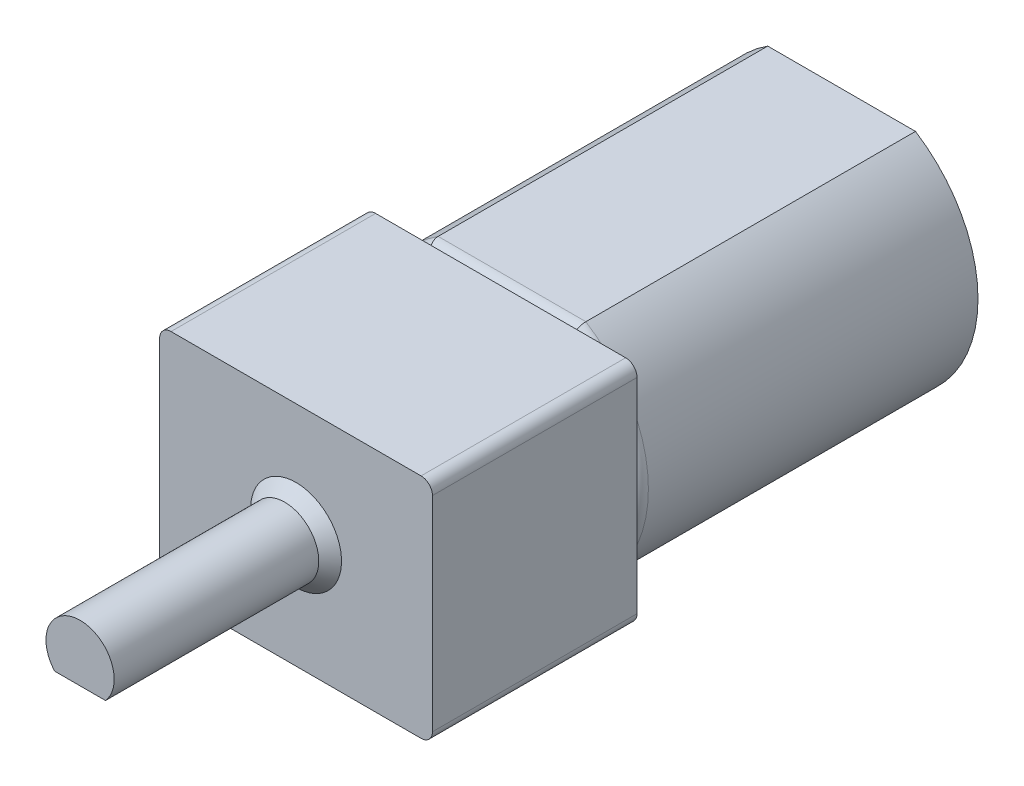
SolidWorks part; units mm, degrees
ref_plane "Front Plane" through (0, 0, 0) normal (0, 0, 1) x (1, 0, 0)
ref_plane "Top Plane" through (0, 0, 0) normal (0, 1, 0) x (1, 0, 0)
ref_plane "Right Plane" through (0, 0, 0) normal (1, 0, 0) x (0, 0, -1)
sketch "Sketch1" plane through (0, 0, 0) normal (0, 0, 1) x (1, 0, 0)
  line L1 (-6, -5) -> (6, -5)
  line L2 (-6, -5) -> (-6, 5)
  line L3 (-6, 5) -> (6, 5)
  line L4 (6, -5) -> (6, 5)
  point P4 (0, 5)
  point P6 (-6, 0)
  point P7 (-5, 2.9184)
  dimension "D1" = 12
  dimension "D2" = 10
extrude "Boss-Extrude1" add sketch "Sketch1" along normal blind 15
sketch "Sketch2" plane through (0, 0, 15) normal (0, 0, 1) x (1, 0, 0)
  line L0 (6, 5) -> (-6, 5) construction
  line L1 (-6, -5) -> (6, -5) construction
  line L2 (-6, 5) -> (-6, -5) construction
  line L3 (0, 6.7983) -> (0, -7.2436) construction
  line L4 (-3.25, 5) -> (-6, 5)
  line L5 (-6, 5) -> (-6, -5)
  line L6 (-6, -5) -> (-3.25, -5)
  arc A0 (-3.25, 5) -> (-3.25, -5) centre (-0.0795, 0) ccw
  line M2 (-6, 5) -> (-6, -5)
  line M3 (-6, -5) -> (6, -5)
  line M5 (6, 5) -> (-6, 5)
  dimension "D1" = 6.5
extrude "Cut-Extrude1" cut sketch "Sketch2" against normal through all contours A0 M5 M2 | A0 L5 M3
mirror "Mirror1" about plane through (0, 0, 0) normal (1, 0, 0) of "Cut-Extrude1"
sketch "Sketch3" plane through (0, 0, 0) normal (0, 0, -1) x (-1, 0, 0)
  circle A0 centre (0, 0) radius 2.5
  dimension "D1" = 5
extrude "Boss-Extrude2" add sketch "Sketch3" along normal blind 1.25
ref_plane "Plane1" through (4, 0, 0) normal (1, 0, 0) x (0, 0, -1)
sketch "Sketch4" plane through (4, 0, 0) normal (1, 0, 0) x (0, 0, -1)
  line L0 (0, -2.5) -> (0, 2.5) construction
  line L1 (0, 0.75) -> (1.25, 0.75)
  line L2 (0, 0.75) -> (0, -0.75)
  line L3 (0, -0.75) -> (1.25, -0.75)
  line L4 (1.25, 0.75) -> (1.25, -0.75)
  line L5 (1.25, -2.5) -> (1.25, 2.5) construction
  circle A0 centre (0.625, 0) radius 0.125
  point P8 (1.25, 0)
  point P12 (0, 0)
  point P13 (0.5197, 0)
  point P14 (0.625, 0.75)
  dimension "D2" = 0.25
  dimension "D1" = 1.5
extrude "Boss-Extrude3" add sketch "Sketch4" against normal blind 0.25 contours L1 L4 L3 L2
mirror "Mirror2" about plane through (0, 0, 0) normal (1, 0, 0) of "Boss-Extrude3"
fillet "Fillet2" radius 0.5 4 edges at (-6, 0, 15) (0, -5, 15) (6, 0, 15) (0, 5, 15)
sketch "Sketch5" plane through (0, 0, 15) normal (0, 0, 1) x (1, 0, 0)
  line L0 (-3.25, -5) -> (-3.0909, -5) construction
  line L1 (-6, 5) -> (6, 5)
  line L2 (-6, 5) -> (-6, -5)
  line L3 (-6, -5) -> (6, -5)
  line L4 (6, 5) -> (6, -5)
  line L5 (3.25, 5) -> (3.0909, 5) construction
  arc A0 (3.25, -5) -> (-3.0909, 5) centre (0.0795, 0) ccw construction
  arc A1 (3.0909, -5) -> (-3.25, 5) centre (-0.0795, 0) ccw construction
extrude "Boss-Extrude4" add sketch "Sketch5" along normal blind 9 contours L2 L3 L4 L1
fillet "Fillet1" radius 0.5 4 edges at (-6, -5, 19.5) (6, -5, 19.5) (6, 5, 19.5) (-6, 5, 19.5)
sketch "Sketch6" plane through (0, 0, 24) normal (0, 0, 1) x (1, 0, 0)
  circle A0 centre (0, 0) radius 1.5
  dimension "D1" = 3
extrude "Boss-Extrude5" add sketch "Sketch6" along normal blind 9.5
chamfer "Chamfer1" distance 0.5 angle 45 1 edges at (1.5, 0, 24)
sketch "Sketch7" plane through (0, 0, 33.5) normal (0, 0, 1) x (1, 0, 0)
  line L0 (-1.118, -1) -> (1.118, -1)
  circle A0 centre (0, 0) radius 1.5 construction
  circle A1 centre (0, 0) radius 1.5 construction
  arc A2 (-1.118, -1) -> (1.118, -1) centre (0, 0) ccw
  dimension "D1" = 2.5
extrude "Cut-Extrude2" cut sketch "Sketch7" against normal blind 6 contours L0 A2
